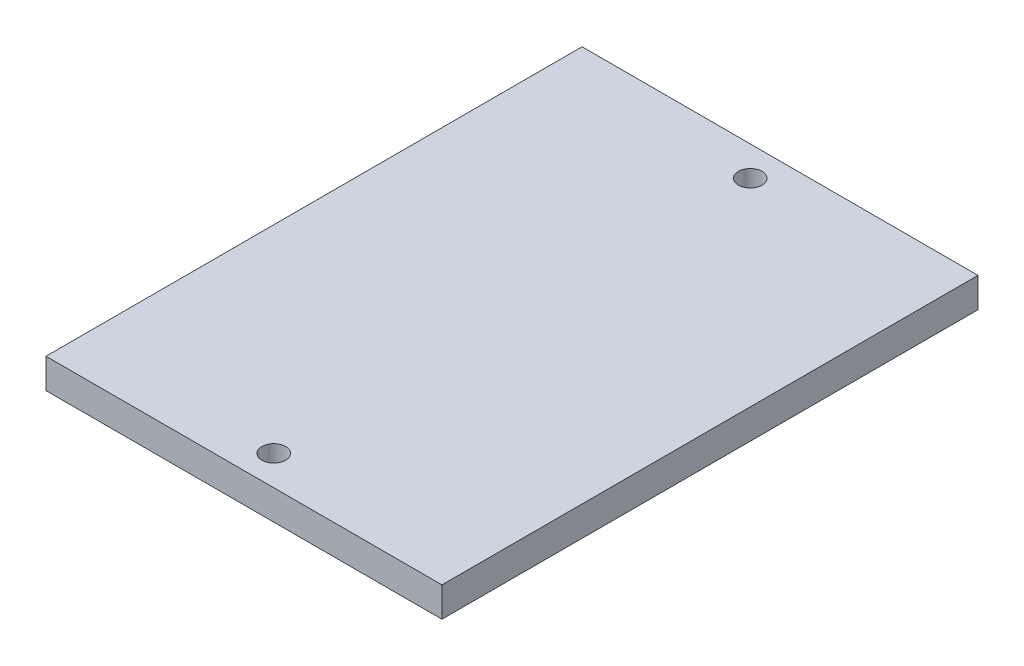
SolidWorks part; units mm, degrees
material "6061 Alloy"
ref_plane "Front" through (0, 0, 0) normal (0, 0, 1) x (1, 0, 0)
ref_plane "Top" through (0, 0, 0) normal (0, 1, 0) x (1, 0, 0)
ref_plane "Right" through (0, 0, 0) normal (1, 0, 0) x (0, 0, -1)
sketch "Sketch1" plane through (0, 0, 0) normal (0, 1, 0) x (1, 0, 0)
  line L1 (-42.2131, -57.15) -> (42.2131, -57.15)
  line L2 (-42.2131, -57.15) -> (-42.2131, 57.15)
  line L3 (-42.2131, 57.15) -> (42.2131, 57.15)
  line L4 (42.2131, -57.15) -> (42.2131, 57.15)
  line L5 (-42.2131, -57.15) -> (42.2131, 57.15) construction
  line L6 (-42.2131, 57.15) -> (42.2131, -57.15) construction
  point P0 (0, 0)
  dimension "D1" = 84.4263
  dimension "D2" = 114.3
extrude "Boss-Extrude1" add sketch "Sketch1" along normal blind 6.35
sketch "Sketch3" plane through (0, 6.35, 0) normal (0, 1, 0) x (1, 0, 0)
  line L0 (42.2131, 57.15) -> (-42.2131, 57.15) construction
  line L1 (-42.2131, 0) -> (42.2131, 0) construction
  line L2 (-42.2131, 57.15) -> (-42.2131, -57.15) construction
  line L3 (42.2131, -57.15) -> (42.2131, 57.15) construction
  circle A4 centre (0, 50.8) radius 2.54
  circle A5 centre (0, -50.8) radius 2.54
  dimension "D1" = 5.08
  dimension "D2" = 6.35
extrude "Cut-Extrude2" cut sketch "Sketch3" against normal blind 9.525
